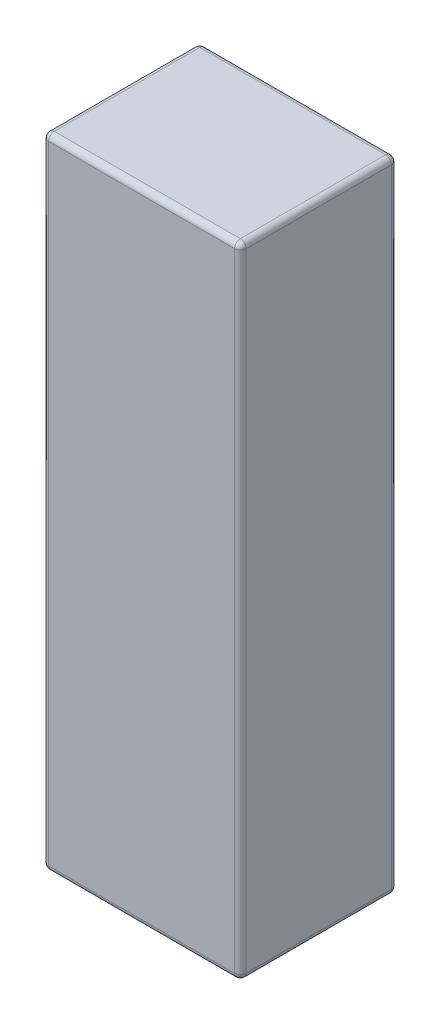
SolidWorks part; units mm, degrees
ref_plane "Ebene vorne" through (0, 0, 0) normal (0, 0, 1) x (1, 0, 0)
ref_plane "Ebene oben" through (0, 0, 0) normal (0, 1, 0) x (1, 0, 0)
ref_plane "Ebene rechts" through (0, 0, 0) normal (1, 0, 0) x (0, 0, -1)
sketch "Skizze1" plane through (0, 0, 0) normal (0, 1, 0) x (1, 0, 0)
  line L0 (0, 6.75) -> (0, -6.75) construction
  line L1 (-8.5, 6.75) -> (8.5, 6.75)
  line L2 (-8.5, 6.75) -> (-8.5, -6.75)
  line L3 (-8.5, -6.75) -> (8.5, -6.75)
  line L4 (8.5, 6.75) -> (8.5, -6.75)
  line L5 (-8.5, 6.75) -> (8.5, -6.75) construction
  line L6 (-8.5, -6.75) -> (8.5, 6.75) construction
  line L7 (-8.5, 0) -> (8.5, 0) construction
  point P0 (0, 0)
  dimension "D1" = 17
  dimension "D2" = 13.5
extrude "Aufsatz-Linear austragen1" add sketch "Skizze1" along normal blind 55
fillet "Verrundung1" radius 0.5 12 edges at (8.5, 55, 0) (0, 55, 6.75) (8.5, 27.5, 6.75) (0, 0, 6.75) (8.5, 0, 0) (-8.5, 55, 0) (-8.5, 27.5, 6.75) (-8.5, 0, 0) (8.5, 27.5, -6.75) (0, 55, -6.75) (-8.5, 27.5, -6.75) (0, 0, -6.75)
